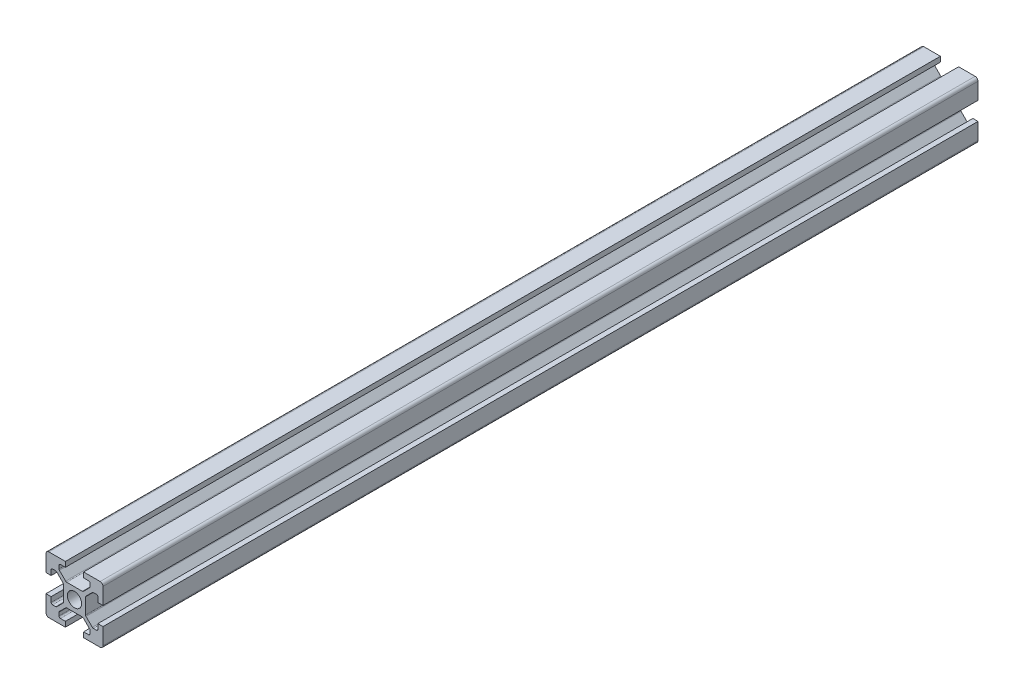
SolidWorks part; units mm, degrees
material "1060 Alloy"
ref_plane "Front Plane" through (0, 0, 0) normal (0, 0, 1) x (1, 0, 0)
ref_plane "Top Plane" through (0, 0, 0) normal (0, 1, 0) x (1, 0, 0)
ref_plane "Right Plane" through (0, 0, 0) normal (1, 0, 0) x (0, 0, -1)
sketch "Sketch1" plane through (0, 0, 0) normal (0, 0, 1) x (1, 0, 0)
  line L0 (20, 0) -> (-8.059, 28.059) construction
  line L1 (0, 0) -> (6.8, 0)
  line L2 (0, 0) -> (0, 6.8)
  line L3 (0, 20) -> (6.8, 20)
  line L4 (20, 0) -> (20, 6.8)
  line L5 (6.8, 20) -> (6.8, 18.2)
  line L6 (20, 20) -> (8.2322, 8.2322) construction
  line L7 (12.95, 6.1) -> (7.05, 6.1)
  line L8 (13.9, 7.05) -> (13.9, 12.95)
  line L9 (12.95, 13.9) -> (7.05, 13.9)
  line L10 (6.1, 7.05) -> (6.1, 12.95)
  line L11 (13.9, 6.1) -> (6.1, 13.9) construction
  line L12 (13.9, 13.9) -> (6.1, 6.1) construction
  line L13 (4.55, 16.4) -> (7.05, 13.9)
  line L14 (13.2, 18.2) -> (13.2, 20)
  line L15 (1.8, 6.8) -> (0, 6.8)
  line L16 (0, 13.2) -> (0, 20)
  line L17 (0, 13.2) -> (1.8, 13.2)
  line L18 (10, 10) -> (10, 13.9) construction
  line L19 (16.4, 4.55) -> (13.9, 7.05)
  line L20 (4.55, 16.4) -> (4.55, 18.2)
  line L21 (4.55, 18.2) -> (6.8, 18.2)
  line L22 (13.2, 18.2) -> (15.45, 18.2)
  line L23 (15.45, 18.2) -> (15.45, 16.4)
  line L24 (15.45, 16.4) -> (12.95, 13.9)
  line L25 (16.4, 4.55) -> (18.2, 4.55)
  line L26 (18.2, 4.55) -> (18.2, 6.8)
  line L27 (20, 6.8) -> (18.2, 6.8)
  line L28 (18.2, 13.2) -> (20, 13.2)
  line L29 (18.2, 13.2) -> (18.2, 15.45)
  line L30 (18.2, 15.45) -> (16.4, 15.45)
  line L31 (16.4, 15.45) -> (13.9, 12.95)
  line L32 (1.8, 4.55) -> (3.6, 4.55)
  line L33 (3.6, 15.45) -> (6.1, 12.95)
  line L34 (3.6, 15.45) -> (1.8, 15.45)
  line L35 (1.8, 15.45) -> (1.8, 13.2)
  line L36 (0, 13.2) -> (1.8, 13.2)
  line L37 (1.8, 6.8) -> (0, 6.8)
  line L38 (3.6, 4.55) -> (6.1, 7.05)
  line L39 (1.8, 6.8) -> (1.8, 4.55)
  line L40 (15.45, 3.6) -> (12.95, 6.1)
  line L41 (4.55, 3.6) -> (7.05, 6.1)
  line L42 (4.55, 1.8) -> (4.55, 3.6)
  line L43 (6.8, 1.8) -> (4.55, 1.8)
  line L44 (6.8, 1.8) -> (6.8, 0)
  line L45 (15.45, 3.6) -> (15.45, 1.8)
  line L46 (15.45, 1.8) -> (13.2, 1.8)
  line L47 (13.2, 0) -> (13.2, 1.8)
  line L48 (13.2, 20) -> (20, 20)
  line L49 (20, 13.2) -> (20, 20)
  line L50 (13.2, 0) -> (20, 0)
  line L51 (6.1, 6.1) -> (-5.5045, -5.5045) construction
  circle A0 centre (10, 10) radius 2.5
  point P25 (10, 16.4)
  point P39 (13.2, 19.1)
  point P46 (0.9, 6.8)
  dimension "D3" = 5
  dimension "D2" = 20
  dimension "D4" = 7.8
  dimension "D5" = 7.8
  dimension "D6" = 6.8
  dimension "D7" = 6.8
  dimension "D8" = 1.8
  dimension "D9" = 10.9
  dimension "D10" = 1.8
  dimension "D11" = 10.9
  dimension "D12" = 20
extrude "Boss-Extrude1" add sketch "Sketch1" along normal blind 307 contours L47 L50 L4 L27 L26 L25 L19 L8 L31 L30 L29 L28 L49 L48 L14 L22 L23 L24 L9 L13 L20 L21 L5 L3 L16 L17 L35 L34 L33 L10 L38 L32 L39 L15 L2 L1 L44 L43 L42 L41 L7 L40 L45 L46 A0
fillet "Fillet1" radius 1 4 edges at (20, 20, 153.5) (20, 0, 153.5) (0, 0, 153.5) (0, 20, 153.5)
fillet "Fillet2" radius 0.5 6 edges at (4.55, 18.2, 153.5) (4.55, 16.4, 153.5) (7.05, 13.9, 153.5) (15.45, 18.2, 153.5) (15.45, 16.4, 153.5) (12.95, 13.9, 153.5)
fillet "Fillet3" radius 0.5 6 edges at (18.2, 15.45, 153.5) (16.4, 15.45, 153.5) (13.9, 12.95, 153.5) (18.2, 4.55, 153.5) (13.9, 7.05, 153.5) (16.4, 4.55, 153.5)
fillet "Fillet4" radius 0.5 6 edges at (1.8, 15.45, 153.5) (3.6, 15.45, 153.5) (6.1, 12.95, 153.5) (3.6, 4.55, 153.5) (1.8, 4.55, 153.5) (6.1, 7.05, 153.5)
fillet "Fillet5" radius 0.5 6 edges at (7.05, 6.1, 153.5) (4.55, 3.6, 153.5) (4.55, 1.8, 153.5) (15.45, 1.8, 153.5) (15.45, 3.6, 153.5) (12.95, 6.1, 153.5)
